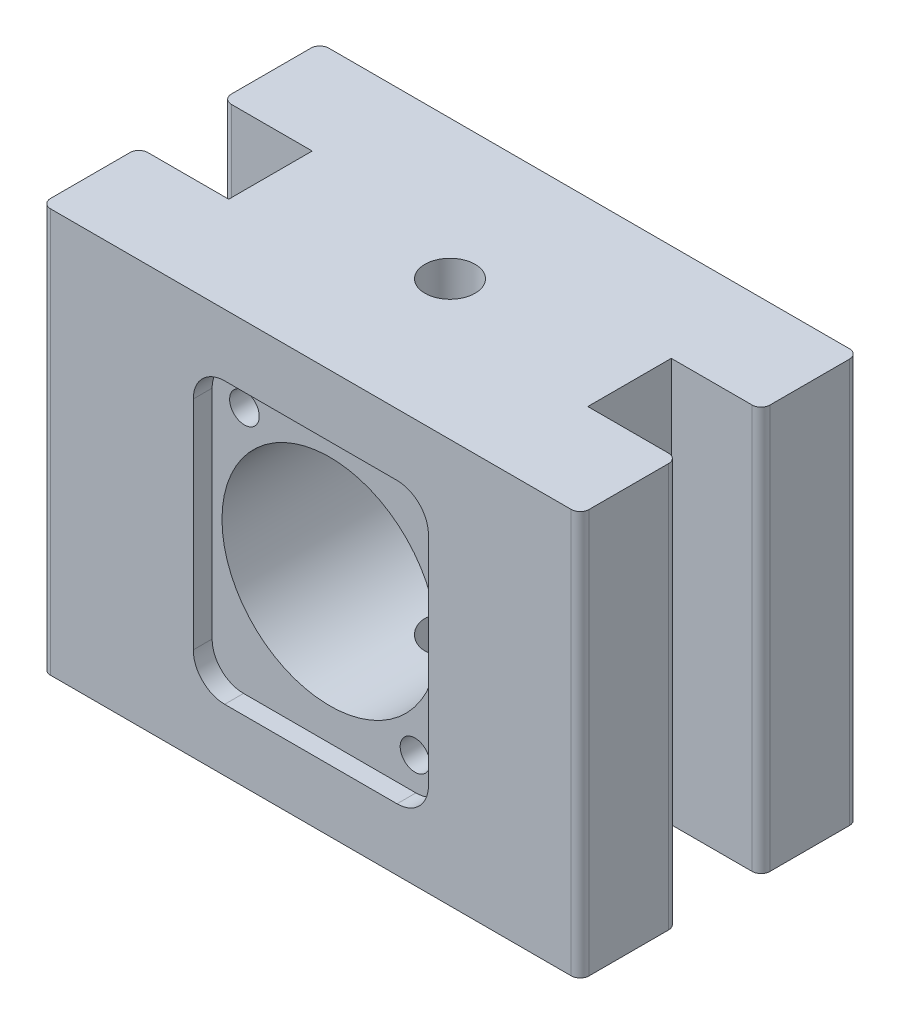
SolidWorks part; units mm, degrees
ref_plane "Front Plane" through (0, 0, 0) normal (0, 0, 1) x (1, 0, 0)
ref_plane "Top Plane" through (0, 0, 0) normal (0, 1, 0) x (1, 0, 0)
ref_plane "Right Plane" through (0, 0, 0) normal (1, 0, 0) x (0, 0, -1)
sketch "Sketch1" plane through (0, 0, 0) normal (0, 1, 0) x (1, 0, 0)
  line L0 (20, 4.65) -> (29, 4.65)
  line L1 (-20, 15.5) -> (20, 15.5)
  line L2 (-20, 4.65) -> (-20, -4.65)
  line L3 (-20, -15.5) -> (20, -15.5)
  line L4 (20, 4.65) -> (20, -4.65)
  line L7 (-29, 15.5) -> (29, 15.5)
  line L8 (-30, 14.5) -> (-30, 5.65)
  line L9 (-29, 4.65) -> (-20, 4.65)
  line L10 (30, 14.5) -> (30, 5.65)
  line L11 (-29, -15.5) -> (29, -15.5)
  line L12 (-30, -14.5) -> (-30, -5.65)
  line L13 (-29, -4.65) -> (-20, -4.65)
  line L14 (30, -14.5) -> (30, -5.65)
  line L15 (20, -4.65) -> (29, -4.65)
  arc A0 (-29, -15.5) -> (-30, -14.5) centre (-29, -14.5) cw
  arc A1 (-30, -5.65) -> (-29, -4.65) centre (-29, -5.65) cw
  arc A2 (-30, 5.65) -> (-29, 4.65) centre (-29, 5.65) ccw
  arc A3 (-29, 15.5) -> (-30, 14.5) centre (-29, 14.5) ccw
  arc A4 (29, -15.5) -> (30, -14.5) centre (29, -14.5) ccw
  arc A5 (29, -4.65) -> (30, -5.65) centre (29, -5.65) cw
  arc A6 (29, 4.65) -> (30, 5.65) centre (29, 5.65) ccw
  arc A7 (29, 15.5) -> (30, 14.5) centre (29, 14.5) cw
  circle A8 centre (0, 0) radius 2.8
  point P0 (0, 0)
  dimension "D6" = 1
  dimension "D7" = 1
  dimension "D8" = 5.6
  dimension "D1" = 40
  dimension "D2" = 31
  dimension "D3" = 9.3
  dimension "D4" = 10
  dimension "D5" = 10
extrude "Boss-Extrude1" add sketch "Sketch1" along normal blind 45 contours A7 L7 L1 A3 L8 A2 L9 L2 L13 A1 L12 A0 L11 L3 A4 L14 A5 L15 L4 L0 A6 L10 A8
sketch "Sketch2" plane through (0, 0, 15.5) normal (0, 0, 1) x (1, 0, 0)
  line L0 (-29, 45) -> (-29, 0) construction
  circle A0 centre (0, 22.5) radius 12
  circle A1 centre (-9.5, 34.5) radius 1.65
  circle A2 centre (9.5, 10.5) radius 1.65
  point P6 (-29, 22.5)
  dimension "D1" = 24
  dimension "D2" = 3.3
  dimension "D3" = 3.3
  dimension "D4" = 19
  dimension "D5" = 24
  dimension "D6" = 9.5
  dimension "D7" = 12
extrude "Cut-Extrude1" cut sketch "Sketch2" against normal blind 56
sketch "Sketch3" plane through (0, 0, 15.5) normal (0, 0, 1) x (1, 0, 0)
  line L1 (-9.6, 38.1) -> (9.6, 38.1)
  line L2 (-13.1, 34.6) -> (-13.1, 10.4)
  line L3 (-9.6, 6.9) -> (9.6, 6.9)
  line L4 (13.1, 34.6) -> (13.1, 10.4)
  line L5 (-13.1, 38.1) -> (13.1, 6.9) construction
  line L6 (-13.1, 6.9) -> (13.1, 38.1) construction
  arc A0 (9.6, 6.9) -> (13.1, 10.4) centre (9.6, 10.4) ccw
  arc A1 (-13.1, 10.4) -> (-9.6, 6.9) centre (-9.6, 10.4) ccw
  arc A2 (9.6, 38.1) -> (13.1, 34.6) centre (9.6, 34.6) cw
  arc A3 (-9.6, 38.1) -> (-13.1, 34.6) centre (-9.6, 34.6) ccw
  point P0 (0, 22.5)
  dimension "D3" = 3.5
  dimension "D1" = 31.2
  dimension "D2" = 26.2
extrude "Cut-Extrude2" cut sketch "Sketch3" against normal blind 2.1 from surface at 0 starting at face at (11.15, 10.5, 15.5)
